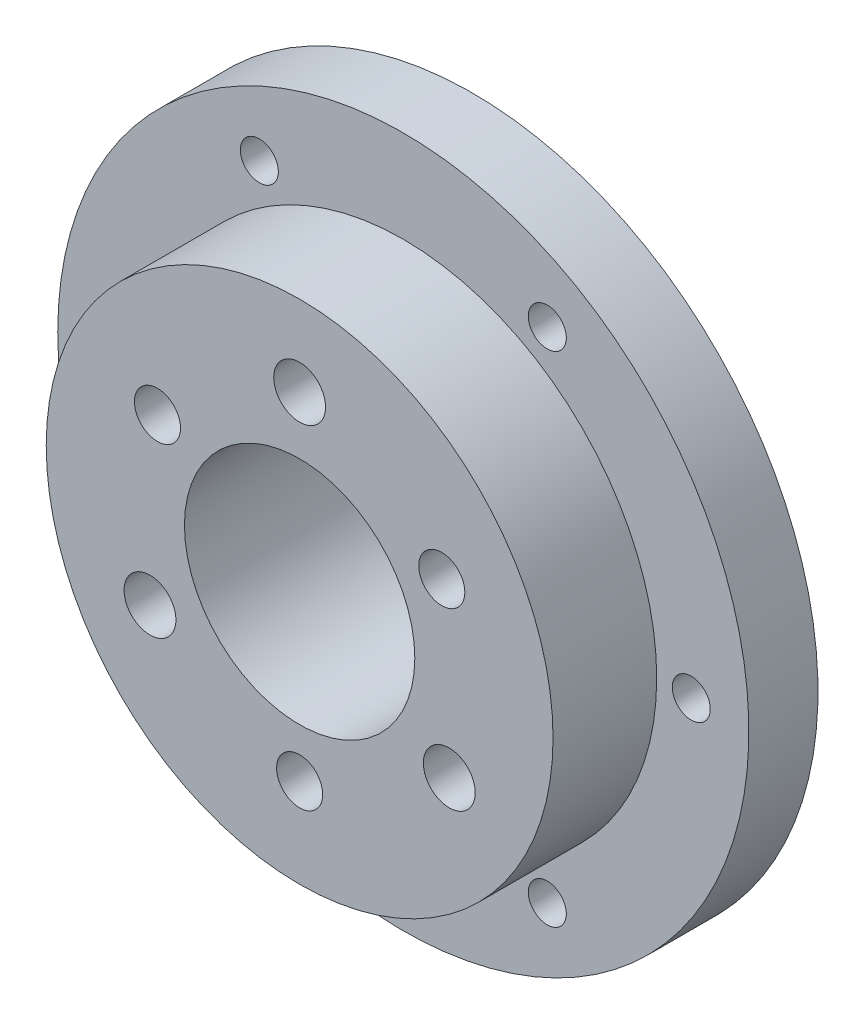
SolidWorks part; units mm, degrees
material "6061-T6 (SS)"
ref_plane "前视基准面" through (0, 0, 0) normal (0, 0, 1) x (1, 0, 0)
ref_plane "上视基准面" through (0, 0, 0) normal (0, 1, 0) x (1, 0, 0)
ref_plane "右视基准面" through (0, 0, 0) normal (1, 0, 0) x (0, 0, -1)
sketch "草图1" plane through (0, 0, 0) normal (0, 0, 1) x (1, 0, 0)
  circle A0 centre (0, 0) radius 22
  dimension "D1" = 44
extrude "凸台-拉伸1" add sketch "草图1" along normal blind 15
sketch "草图6" plane through (0, 0, 0) normal (0, 0, -1) x (-1, 0, 0)
  circle A0 centre (0, 0) radius 30
  dimension "D1" = 60
extrude "凸台-拉伸2" add sketch "草图6" against normal blind 6
sketch "草图2" plane through (0, 0, 15) normal (0, 0, 1) x (1, 0, 0)
  line L0 (0, 22) -> (0, 0) construction
  line L1 (12.9904, -7.5) -> (-12.3409, 7.125) construction
  circle A1 centre (0, 0) radius 22 construction
  circle A5 centre (0, 0) radius 14.25 construction
  circle A6 centre (-12.3409, 7.125) radius 2
  circle A7 centre (12.3409, 7.125) radius 2
  circle A8 centre (0, -14.25) radius 2
  dimension "D4" = 28.5
  dimension "D5" = 4
  dimension "D6" = 3
extrude "切除-拉伸1" cut sketch "草图2" against normal through all both and the other way through all
sketch "草图3" plane through (0, 0, 0) normal (0, 0, -1) x (-1, 0, 0)
  circle A0 centre (0, 0) radius 10
  dimension "D1" = 20
extrude "切除-拉伸2" cut sketch "草图3" against normal through all
sketch "草图4" plane through (0, 0, 0) normal (0, 0, -1) x (-1, 0, 0)
  circle A0 centre (0, 0) radius 15 construction
  point P3 (0, 15)
  point P5 (-12.9904, 7.5)
  point P7 (12.9904, -7.5)
  point P9 (-12.9904, -7.5)
  point P11 (12.9904, 7.5)
  point P12 (0, -15)
  dimension "D1" = 30
  dimension "D2" = 6
hole_wizard "打孔尺寸(%根据)内六角圆柱头螺钉的类型1" positions "3D草图1" profile "草图5" counterbore size "M4" standard "GB" end condition through all
sketch3d "3D草图1"
  point P0 (12.9904, -7.5, 0)
  point P3 (-12.9904, -7.5, 0)
  point P6 (0, 15, 0)
sketch "草图5" plane through (12.9904, -7.5, 0) normal (1, 0, 0) x (0, 1, 0)
  line L0 (0, 0) -> (0, 15)
  line L1 (0, 15) -> (2.25, 15)
  line L3 (2.25, 15) -> (2.25, 4.6)
  line L4 (2.25, 4.6) -> (4, 4.6)
  line L5 (4, 4.6) -> (4, 0)
  line L7 (4, 0) -> (0, 0)
  line L11 (0, -6.35) -> (0, 107.95) construction
  dimension "通孔孔直径" = 4.5
  dimension "通孔孔深度" = 15
  dimension "柱形沉头孔直径" = 8
  dimension "柱形沉头孔深度" = 4.6
sketch "草图7" plane through (0, 0, 0) normal (0, 0, -1) x (-1, 0, 0)
  circle A0 centre (0, 0) radius 25 construction
  circle A1 centre (0, 0) radius 10 construction
  point P3 (-25, 0)
  point P7 (-12.5, 21.6506)
  point P8 (12.5, 21.6506)
  point P9 (25, 0)
  point P10 (12.5, -21.6506)
  point P11 (-12.5, -21.6506)
  dimension "D1" = 50
  dimension "D2" = 6
hole_wizard "M4 螺纹孔1" positions "3D草图2" profile "草图8" tap size "M4" standard "GB" end condition through all
sketch3d "3D草图2"
  point P0 (25, 0, 0)
  point P3 (12.5, 21.6506, 0)
  point P6 (-12.5, 21.6506, 0)
  point P9 (-25, 0, 0)
  point P12 (-12.5, -21.6506, 0)
  point P15 (12.5, -21.6506, 0)
sketch "草图8" plane through (25, 0, 0) normal (1, 0, 0) x (0, 1, 0)
  line L0 (0, 0) -> (0, 15)
  line L1 (0, 15) -> (1.65, 15)
  line L2 (1.65, 15) -> (1.65, 0)
  line L5 (1.65, 0) -> (0, 0)
  line L11 (0, -6.35) -> (0, 107.95) construction
  dimension "通孔螺纹孔钻头直径" = 3.3
  dimension "通孔螺纹孔钻头深度" = 15
cosmetic thread "孔螺蚊线1" parameters "D2"=4
cosmetic thread "孔螺蚊线2" parameters "D2"=4
cosmetic thread "孔螺蚊线3" parameters "D2"=4
cosmetic thread "孔螺蚊线4" parameters "D2"=4
cosmetic thread "孔螺蚊线5" parameters "D2"=4
cosmetic thread "孔螺蚊线6" parameters "D2"=4
